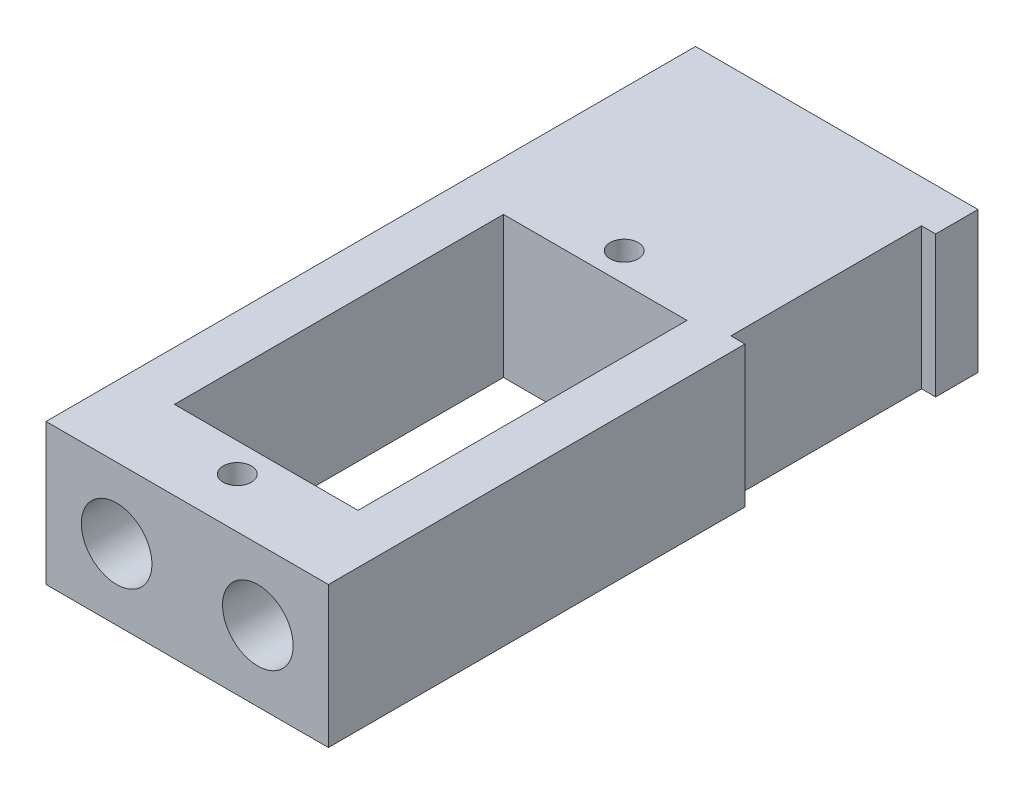
SolidWorks part; units mm, degrees
ref_plane "Front Plane" through (0, 0, 0) normal (0, 0, 1) x (1, 0, 0)
ref_plane "Top Plane" through (0, 0, 0) normal (0, 1, 0) x (1, 0, 0)
ref_plane "Right Plane" through (0, 0, 0) normal (1, 0, 0) x (0, 0, -1)
sketch "Sketch1" plane through (0, 0, 0) normal (0, 1, 0) x (1, 0, 0)
  line L1 (-10, 23) -> (10, 23)
  line L2 (-10, 23) -> (-10, -23)
  line L3 (-10, -23) -> (10, -23)
  line L4 (10, 23) -> (10, -23)
  line L5 (-10, 23) -> (10, -23) construction
  line L6 (-10, -23) -> (10, 23) construction
  point P0 (0, 0)
  dimension "D1" = 20
  dimension "D2" = 46
extrude "Boss-Extrude1" add sketch "Sketch1" along normal blind 10
sketch "Sketch2" plane through (0, 10, 0) normal (0, 1, 0) x (1, 0, 0)
  line L0 (6.5, -5.755) -> (-6.5, -5.755) construction
  line L1 (-6.5, 5.895) -> (6.5, 5.895)
  line L2 (-6.5, 5.895) -> (-6.5, -17.405)
  line L3 (-6.5, -17.405) -> (6.5, -17.405)
  line L4 (6.5, 5.895) -> (6.5, -17.405)
  line L5 (-6.5, 5.895) -> (6.5, -17.405) construction
  line L6 (-6.5, -17.405) -> (6.5, 5.895) construction
  line L7 (10, 0) -> (-10, 0) construction
  line L8 (10, -23) -> (10, 23) construction
  line L9 (-10, 23) -> (-10, -23) construction
  line L10 (0, 23) -> (0, -23) construction
  line L11 (10, 23) -> (-10, 23) construction
  line L12 (-10, -23) -> (10, -23) construction
  circle A0 centre (0, 7.945) radius 1
  circle A1 centre (0, -19.455) radius 1
  point P0 (0, -5.755)
  dimension "D4" = 2
  dimension "D1" = 17.405
  dimension "D2" = 13
  dimension "D3" = 23.3
  dimension "D5" = 27.4
extrude "Cut-Extrude1" cut sketch "Sketch2" against normal through all
sketch "Sketch3" plane through (0, 0, -23) normal (0, 0, -1) x (-1, 0, 0)
  line L0 (10, 5) -> (-10, 5) construction
  line L1 (10, 10) -> (10, 0) construction
  line L2 (-10, 10) -> (-10, 0) construction
  line L3 (0, 0) -> (0, 10) construction
  line L4 (-10, 0) -> (10, 0) construction
  line L5 (-10, 10) -> (10, 10) construction
  circle A0 centre (5, 5) radius 2.5
  circle A1 centre (-5, 5) radius 2.5
  dimension "D1" = 5
  dimension "D2" = 10
extrude "Cut-Extrude2" cut sketch "Sketch3" against normal blind 4
sketch "Sketch4" plane through (0, 0, 23) normal (0, 0, 1) x (1, 0, 0)
  line L0 (20, 5) -> (-20, 5) construction
  line L3 (0, 0) -> (0, 10) construction
  circle A0 centre (5, 5) radius 2.5
  circle A1 centre (-5, 5) radius 2.5
  dimension "D1" = 5
  dimension "D2" = 10
extrude "Cut-Extrude3" cut sketch "Sketch4" against normal blind 4
sketch "Sketch5" plane through (10, 0, 0) normal (1, 0, 0) x (0, 0, -1)
  line L0 (-23, 0) -> (23, 0) construction
  line L1 (20, 0) -> (6.5, 0)
  line L2 (20, 0) -> (20, 10)
  line L3 (20, 10) -> (6.5, 10)
  line L4 (6.5, 0) -> (6.5, 10)
  line L5 (-23, 10) -> (23, 10) construction
  line L6 (23, 10) -> (23, 0) construction
  dimension "D1" = 13.5
  dimension "D2" = 3
extrude "Cut-Extrude4" cut sketch "Sketch5" against normal blind 1
